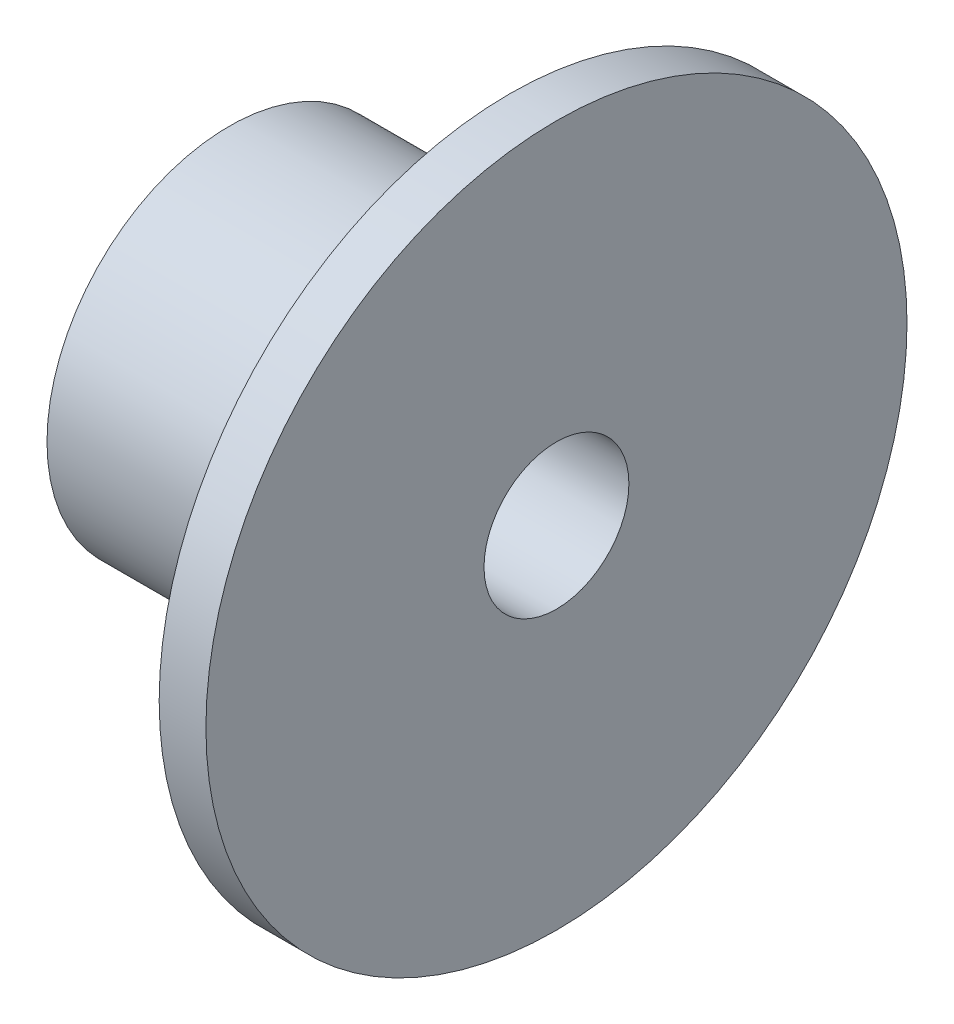
SolidWorks part; units mm, degrees
ref_plane "Plano frontal" through (0, 0, 0) normal (0, 0, 1) x (1, 0, 0)
ref_plane "Plano superior" through (0, 0, 0) normal (0, 1, 0) x (1, 0, 0)
ref_plane "Plano direito" through (0, 0, 0) normal (1, 0, 0) x (0, 0, -1)
sketch "Esboço1" plane through (0, 0, 0) normal (1, 0, 0) x (0, 0, -1)
  circle A0 centre (0, 0) radius 1.55
  circle A1 centre (0, 0) radius 3.9
  dimension "D1" = 7.8
  dimension "D2" = 3.1
extrude "Ressalto-extrusão1" add sketch "Esboço1" along normal blind 6
sketch "Esboço2" plane through (6, 0, 0) normal (1, 0, 0) x (0, 0, -1)
  circle A0 centre (0, 0) radius 7.5
  circle A1 centre (0, 0) radius 1.55 construction
  circle A2 centre (0, 0) radius 1.55
  dimension "D1" = 15
extrude "Ressalto-extrusão2" add sketch "Esboço2" along normal blind 1
sketch "Esboço3" plane through (0, 0, 0) normal (-1, 0, 0) x (0, 0, 1)
  line L1 (1.7032, -2.95) -> (3.4064, 0)
  line L2 (3.4064, 0) -> (1.7032, 2.95)
  line L3 (1.7032, 2.95) -> (-1.7032, 2.95)
  line L4 (-1.7032, 2.95) -> (-3.4064, 0)
  line L5 (-3.4064, 0) -> (-1.7032, -2.95)
  line L6 (-1.7032, -2.95) -> (1.7032, -2.95)
  circle A0 centre (0, 0) radius 2.95 construction
  dimension "D1" = 5.9
extrude "Corte-extrusão1" cut sketch "Esboço3" against normal blind 3
fillet "Filete1" radius 1 1 edges at (6, 0, -3.9)
